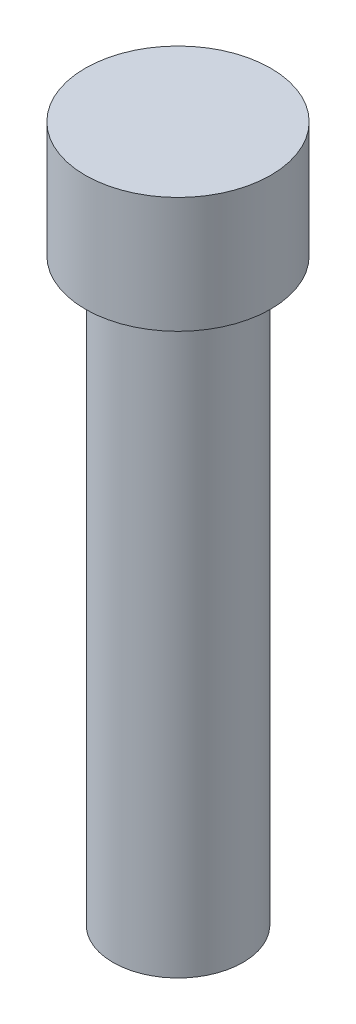
SolidWorks part; units mm, degrees
ref_plane "前视基准面" through (0, 0, 0) normal (0, 0, 1) x (1, 0, 0)
ref_plane "上视基准面" through (0, 0, 0) normal (0, 1, 0) x (1, 0, 0)
ref_plane "右视基准面" through (0, 0, 0) normal (1, 0, 0) x (0, 0, -1)
other "Configuration Table"
sketch "草图1" plane through (0, 0, 0) normal (0, 1, 0) x (1, 0, 0)
  circle A0 centre (0, 0) radius 2.8
  dimension "D1" = 5.6
extrude "凸台-拉伸1" add sketch "草图1" along normal blind 25 contours A0
sketch "草图2" plane through (0, 25, 0) normal (0, 1, 0) x (1, 0, 0)
  circle A0 centre (0, 0) radius 4
  dimension "D1" = 8
extrude "凸台-拉伸2" add sketch "草图2" along normal blind 5
